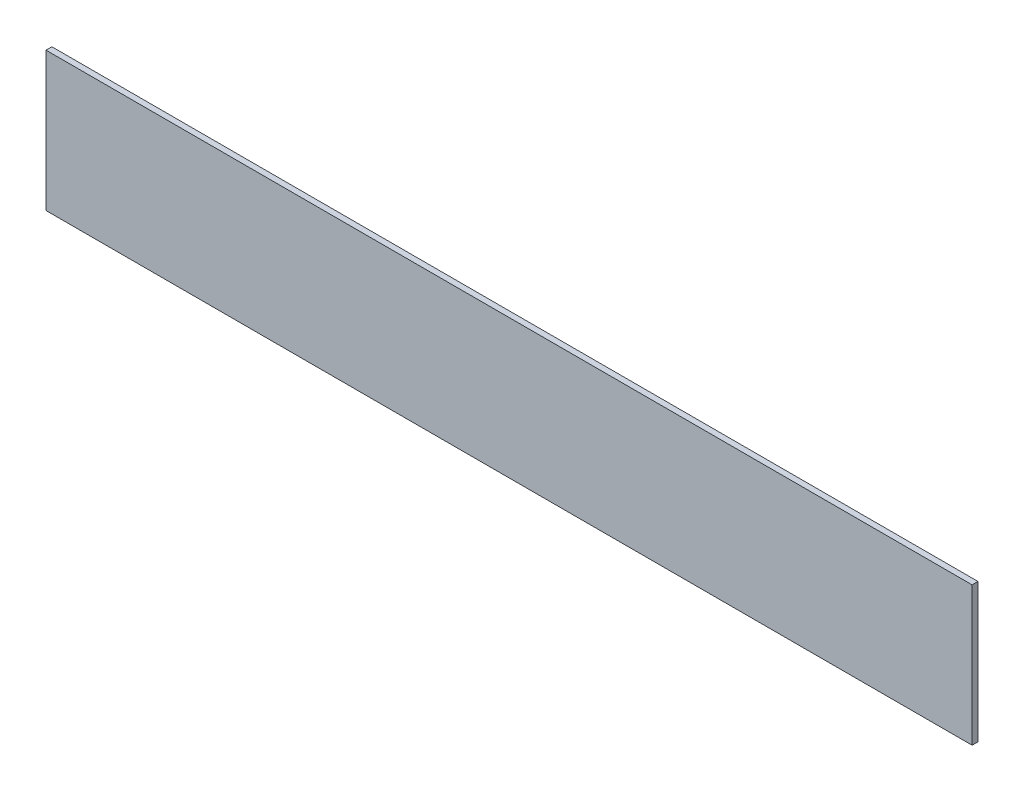
SolidWorks part; units mm, degrees
ref_plane "Alzado" through (0, 0, 0) normal (0, 0, 1) x (1, 0, 0)
ref_plane "Planta" through (0, 0, 0) normal (0, 1, 0) x (1, 0, 0)
ref_plane "Vista lateral" through (0, 0, 0) normal (1, 0, 0) x (0, 0, -1)
sketch "Croquis1" plane through (0, 0, 0) normal (0, 0, 1) x (1, 0, 0)
  line L1 (-250, -37.5) -> (250, -37.5)
  line L2 (-250, -37.5) -> (-250, 37.5)
  line L3 (-250, 37.5) -> (250, 37.5)
  line L4 (250, -37.5) -> (250, 37.5)
  line L5 (-250, -37.5) -> (250, 37.5) construction
  line L6 (-250, 37.5) -> (250, -37.5) construction
  point P0 (0, 0)
  dimension "D1" = 75
  dimension "D2" = 500
extrude "Saliente-Extruir1" add sketch "Croquis1" along normal mid plane 3.175
